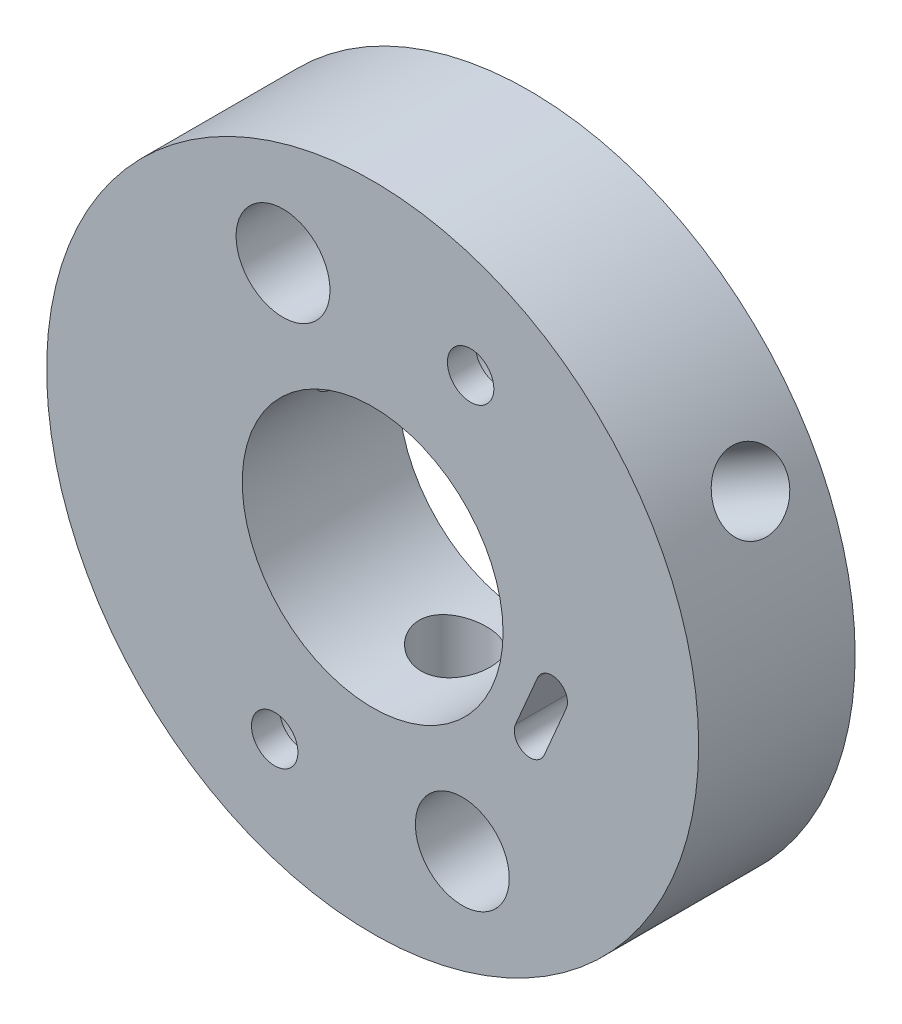
SolidWorks part; units mm, degrees
ref_plane "Front Plane" through (0, 0, 0) normal (0, 0, 1) x (1, 0, 0)
ref_plane "Top Plane" through (0, 0, 0) normal (0, 1, 0) x (1, 0, 0)
ref_plane "Right Plane" through (0, 0, 0) normal (1, 0, 0) x (0, 0, -1)
sketch "Sketch1" plane through (0, 0, 0) normal (0, 0, 1) x (1, 0, 0)
  circle A0 centre (0, 0) radius 15.875
  dimension "D1" = 31.75
extrude "Boss-Extrude1" add sketch "Sketch1" along normal blind 7.62
sketch "Sketch2" plane through (0, 0, 7.62) normal (0, 0, 1) x (1, 0, 0)
  circle A0 centre (0, 0) radius 6.35
  dimension "D1" = 12.7
extrude "Cut-Extrude1" cut sketch "Sketch2" against normal through all
ref_plane "Plane1" through (0, 0, 3.81) normal (0, 0, 1) x (1, 0, 0)
sketch "Sketch11" plane through (0, 0, 3.81) normal (0, 0, 1) x (1, 0, 0)
  point P0 (-31.3984, 15.2938)
  point P1 (31.3893, 15.3123)
  point P3 (0, -34.925)
sketch "Sketch33" plane through (0, 0, 7.62) normal (0, 0, 1) x (1, 0, 0)
  line L0 (-7.6406, 13.9153) -> (7.6406, -13.9153)
  circle A0 centre (0, 0) radius 15.875 construction
sketch "Sketch34" plane through (0, 0, 7.62) normal (0, 0, 1) x (1, 0, 0)
  line L0 (7.6406, -13.9153) -> (3.048, -5.5707)
  line L1 (-7.6406, 13.9153) -> (-10.7006, 19.4883)
  circle A0 centre (0, 0) radius 6.35 construction
  point P8 (5.3443, -9.743)
  point P9 (-9.1706, 16.7018)
ref_plane "Plane2" through (0, -15.875, 0) normal (0, -1, 0) x (-1, 0, 0)
hole_wizard "Tap Drill for #8-32 Tap1" positions "Sketch35" profile "Sketch36" hole size "#8-32" standard "ANSI Inch"
sketch "Sketch35" plane through (0, -15.875, 0) normal (0, -1, 0) x (-1, 0, 0)
  line L0 (17.4625, -3.175) -> (-17.4625, -3.175) construction
  point P0 (0.4504, -3.175)
sketch "Sketch36" plane through (-0.4504, -15.875, 3.175) normal (1, 0, 0) x (0, 0, -1)
  line L0 (0, 0) -> (0, 20.4993)
  line L1 (0, 20.4993) -> (1.7272, 19.05)
  line L2 (1.7272, 19.05) -> (1.7272, 0)
  line L5 (1.7272, 0) -> (0, 0)
  line L10 (0, 20.4993) -> (-1.7272, 19.05) construction
  line L11 (0, -6.35) -> (0, 107.95) construction
  dimension "Hole Dia." = 3.4544
  dimension "Hole Depth" = 19.05
  dimension "Drill Angle" = 100
pattern_circular "CirPattern1" count 3 over 360 about axis through (0, 0, 7.62) along (0, 0, -1) of "Tap Drill for #8-32 Tap1"
sketch "Sketch37" plane through (0, 0, 0) normal (0, 0, -1) x (-1, 0, 0)
  line L0 (0, 0) -> (-12.587, -13.4418)
  dimension "D2" = 18.415
sketch "Sketch38" plane through (0, 0, 0) normal (0, 0, -1) x (-1, 0, 0)
  line L0 (0, 0) -> (-6.4423, 9.0545)
  dimension "D1" = 11.1125
ref_point "Point1"
sketch "Sketch39" plane through (0, 0, 0) normal (0, 0, -1) x (-1, 0, 0)
  line L0 (0, 0) -> (4.7696, -10.0509)
  dimension "D1" = 11.1252
hole_wizard "CBORE for #2 Button Head Cap Screw1" positions "Sketch40" profile "Sketch41" counterbore size "#2" standard "ANSI Inch" end condition through all
sketch "Sketch40" plane through (0, 0, 0) normal (0, 0, -1) x (-1, 0, 0)
  point P0 (4.7696, -10.0509)
sketch "Sketch41" plane through (-4.7696, -10.0509, 0) normal (1, 0, 0) x (0, 1, 0)
  line L0 (0, 0) -> (0, 7.62)
  line L1 (0, 7.62) -> (1.1303, 7.62)
  line L3 (1.1303, 7.62) -> (1.1303, 6.2484)
  line L4 (1.1303, 6.2484) -> (2.5794, 6.2484)
  line L5 (2.5794, 6.2484) -> (2.5794, 0)
  line L7 (2.5794, 0) -> (0, 0)
  line L11 (0, -6.35) -> (0, 107.95) construction
  dimension "Thru Hole Dia." = 2.2606
  dimension "Thru Hole Depth" = 7.62
  dimension "C'Bore Dia." = 5.1587
  dimension "C'Bore Depth" = 6.2484
pattern_circular "CirPattern2" count 2 over 360 about axis through (0, 0, 0) along (0, 0, 1) of "CBORE for #2 Button Head Cap Screw1"
sketch "Sketch42" plane through (0, 0, 0) normal (0, 0, -1) x (-1, 0, 0)
  line L0 (0, 0) -> (4.3654, 10.2192)
  circle A0 centre (4.3654, 10.2192) radius 2.286
extrude "Cut-Extrude2" cut sketch "Sketch42" against normal blind 7.62 contours A0
pattern_circular "CirPattern3" count 2 over 360 about axis through (0, 0, 0) along (0, 0, 1) of "Cut-Extrude2"
sketch "Sketch43" plane through (0, 0, 0) normal (0, 0, -1) x (-1, 0, 0)
  line L0 (-8.7244, -1.373) -> (-7.6557, -3.8635)
  line L1 (-8.7244, -1.373) -> (-7.6557, -3.8635) construction
  line L2 (-8.0257, -1.0731) -> (-6.957, -3.5637)
  line L3 (-9.4232, -1.6728) -> (-8.3545, -4.1634)
  arc A0 (-8.0257, -1.0731) -> (-9.4232, -1.6728) centre (-8.7244, -1.373) ccw
  arc A1 (-8.3545, -4.1634) -> (-6.957, -3.5637) centre (-7.6557, -3.8635) ccw
  point P2 (-8.1901, -2.6183)
  dimension "D1" = 2.7102
extrude "Cut-Extrude3" cut sketch "Sketch43" against normal through all contours L3 A1 L2 A0
ref_plane "Plane3" through (0, 0, 3.175) normal (0, 0, -1) x (-1, 0, 0)
